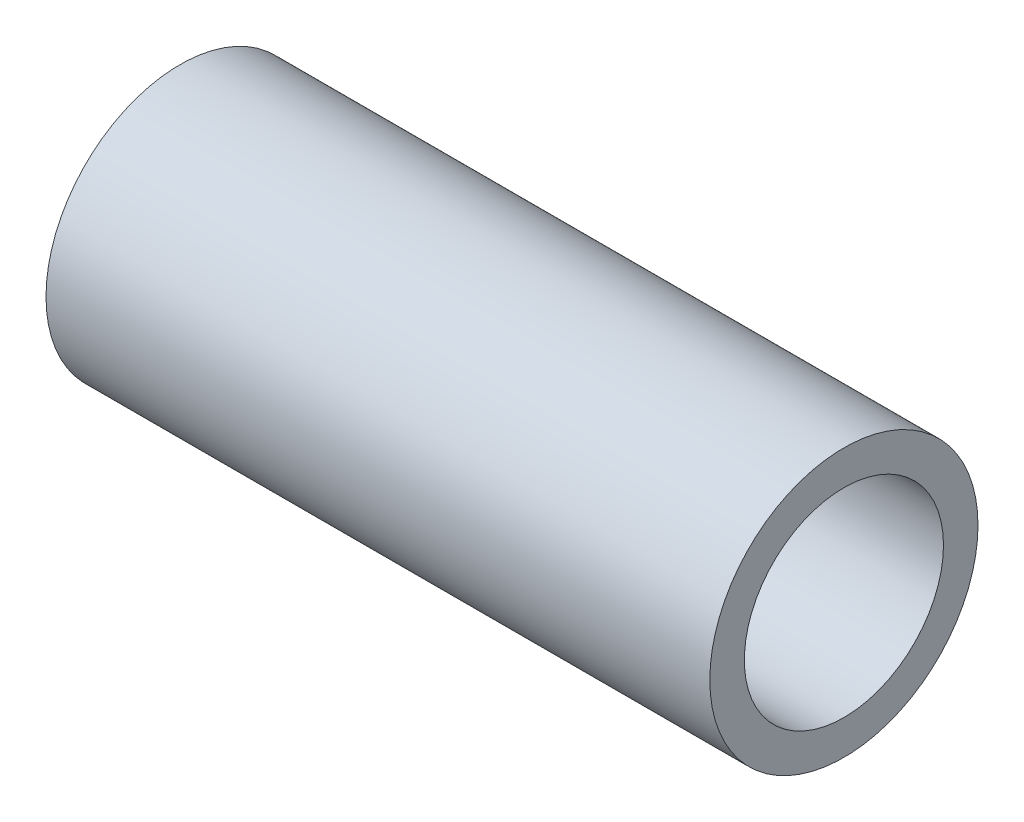
SolidWorks part; units mm, degrees
ref_plane "Front Plane" through (0, 0, 0) normal (0, 0, 1) x (1, 0, 0)
ref_plane "Top Plane" through (0, 0, 0) normal (0, 1, 0) x (1, 0, 0)
ref_plane "Right Plane" through (0, 0, 0) normal (1, 0, 0) x (0, 0, -1)
sketch "Sketch1" plane through (0, 0, 0) normal (1, 0, 0) x (0, 0, -1)
  circle A0 centre (0, 0) radius 10.1
  circle A1 centre (0, 0) radius 7.5
  dimension "D1" = 20.2
  dimension "D2" = 15
extrude "Boss-Extrude1" add sketch "Sketch1" along normal blind 50
